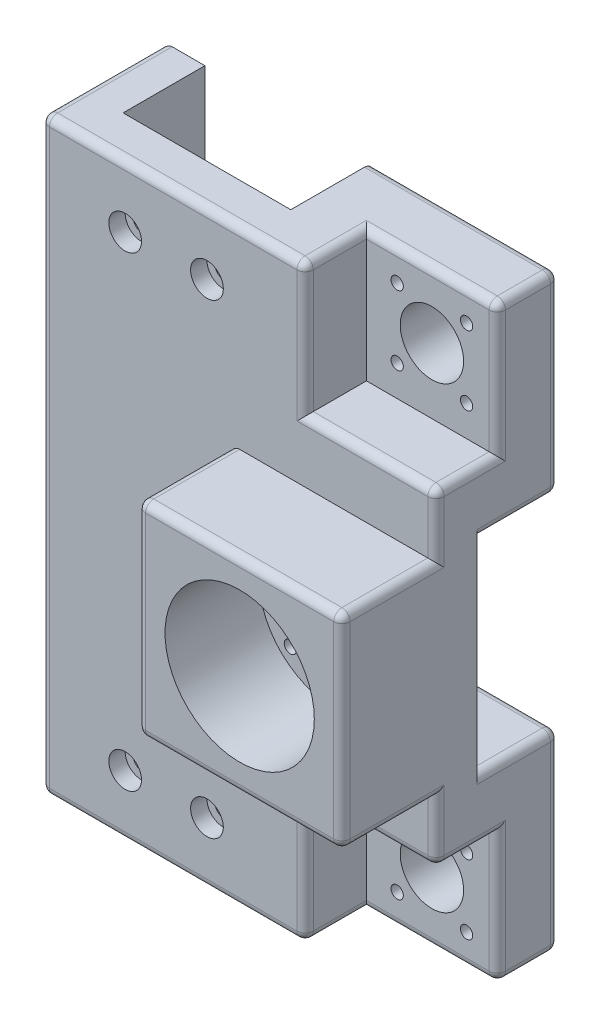
SolidWorks part; units mm, degrees
ref_plane "Front" through (0, 0, 0) normal (0, 0, 1) x (1, 0, 0)
ref_plane "Top" through (0, 0, 0) normal (0, 1, 0) x (1, 0, 0)
ref_plane "Right" through (0, 0, 0) normal (1, 0, 0) x (0, 0, -1)
sketch "Sketch2" plane through (0, 0, 0) normal (0, 0, 1) x (1, 0, 0)
  line L0 (27.25, 72) -> (-59.25, 72)
  line L1 (-43.25, 0) -> (34.25, 0)
  line L3 (12.75, 21.5) -> (55.75, 21.5)
  line L4 (12.75, 21.5) -> (12.75, -21.5)
  line L5 (12.75, -21.5) -> (55.75, -21.5)
  line L6 (55.75, 21.5) -> (55.75, -21.5)
  line L7 (27.25, 72) -> (59.25, 72)
  line L8 (27.25, 72) -> (27.25, 40)
  line L9 (27.25, 40) -> (59.25, 40)
  line L10 (59.25, 72) -> (59.25, 40)
  line L11 (12.75, 21.5) -> (55.75, -21.5) construction
  line L12 (12.75, -21.5) -> (55.75, 21.5) construction
  line L13 (27.25, -40) -> (59.25, -40)
  line L14 (27.25, -40) -> (27.25, -72)
  line L15 (27.25, -72) -> (59.25, -72)
  line L16 (59.25, -40) -> (59.25, -72)
  line L19 (-59.25, 16) -> (-27.25, 16)
  line L20 (-59.25, 16) -> (-59.25, -16)
  line L21 (-59.25, -16) -> (-27.25, -16)
  line L22 (-27.25, 16) -> (-27.25, -16)
  line L25 (-59.25, 72) -> (-59.25, -72)
  line L26 (-59.25, -72) -> (27.25, -72)
  line L27 (59.25, -40) -> (59.25, 40)
  point P0 (0, 0)
  point P14 (-43.25, 0)
sketch "Sketch3" plane through (0, 0, 0) normal (0, 0, 1) x (1, 0, 0)
  line L0 (-59.25, 72) -> (-59.25, -72)
  line L1 (-59.25, -72) -> (59.25, -72)
  line L2 (59.25, -72) -> (59.25, 72)
  line L3 (59.25, 72) -> (-59.25, 72)
extrude "Boss-Extrude1" add sketch "Sketch3" against normal blind 30
sketch "Sketch4" plane through (0, 0, 0) normal (0, 0, 1) x (1, 0, 0)
  circle A0 centre (34.25, 0) radius 11
extrude "Cut-Extrude1" cut sketch "Sketch4" against normal blind 2
sketch "Sketch5" plane through (0, 0, -2) normal (0, 0, 1) x (1, 0, 0)
  circle A0 centre (34.25, 0) radius 4
extrude "Cut-Extrude2" cut sketch "Sketch5" against normal blind 30
sketch "Sketch7" plane through (0, 0, -30) normal (0, 0, -1) x (-1, 0, 0)
  line L2 (27.25, -88.8841) -> (-13.75, -88.8841)
  line L3 (27.25, -88.8841) -> (27.25, 88.8841)
  line L4 (27.25, 88.8841) -> (-13.75, 88.8841)
  line L5 (-13.75, -88.8841) -> (-13.75, 88.8841)
  line L6 (27.25, -88.8841) -> (-13.75, 88.8841) construction
  line L7 (27.25, 88.8841) -> (-13.75, -88.8841) construction
extrude "Cut-Extrude4" cut sketch "Sketch7" against normal blind 20
sketch "Sketch8" plane through (0, 0, -30) normal (0, 0, -1) x (-1, 0, 0)
  line L1 (8.7589, 25) -> (-77.2589, 25)
  line L2 (8.7589, 25) -> (8.7589, -25)
  line L3 (8.7589, -25) -> (-77.2589, -25)
  line L4 (-77.2589, 25) -> (-77.2589, -25)
  line L5 (8.7589, 25) -> (-77.2589, -25) construction
  line L6 (8.7589, -25) -> (-77.2589, 25) construction
  point P0 (-34.25, 0)
extrude "Cut-Extrude5" cut sketch "Sketch8" against normal blind 20
sketch "Sketch9" plane through (0, 0, 0) normal (0, 0, 1) x (1, 0, 0)
  circle A0 centre (-43.25, 0) radius 7.5
  circle A1 centre (43.25, -56) radius 7.5
  circle A2 centre (43.25, 56) radius 7.5
extrude "Cut-Extrude6" cut sketch "Sketch9" against normal blind 30
sketch "Sketch10" plane through (0, 0, 0) normal (0, 0, 1) x (1, 0, 0)
  line L1 (-59.25, 16) -> (-27.25, 16)
  line L2 (-59.25, 16) -> (-59.25, -16)
  line L3 (-59.25, -16) -> (-27.25, -16)
  line L4 (-27.25, 16) -> (-27.25, -16)
  line L5 (-59.25, 16) -> (-27.25, -16) construction
  line L6 (-59.25, -16) -> (-27.25, 16) construction
  line L7 (27.25, 72) -> (59.25, 72)
  line L8 (27.25, 72) -> (27.25, 40)
  line L9 (27.25, 40) -> (59.25, 40)
  line L10 (59.25, 72) -> (59.25, 40)
  line L11 (27.25, 72) -> (59.25, 40) construction
  line L12 (27.25, 40) -> (59.25, 72) construction
  line L13 (27.25, -40) -> (59.25, -40)
  line L14 (27.25, -40) -> (27.25, -72)
  line L15 (27.25, -72) -> (59.25, -72)
  line L16 (59.25, -40) -> (59.25, -72)
  line L17 (27.25, -40) -> (59.25, -72) construction
  line L18 (27.25, -72) -> (59.25, -40) construction
  point P0 (-43.25, 0)
  point P7 (43.25, 56)
  point P14 (43.25, -56)
extrude "Cut-Extrude7" cut sketch "Sketch10" against normal blind 15
sketch "Sketch14" plane through (0, 0, -10) normal (0, 0, -1) x (-1, 0, 0)
  circle A0 centre (16.75, 0) radius 2
  circle A1 centre (-3.25, 0) radius 2
  circle A2 centre (16.75, 57) radius 2
  circle A3 centre (-3.25, 57) radius 2
  circle A4 centre (16.75, -57) radius 2
  circle A5 centre (-3.25, -57) radius 2
  point P6 (6.75, 0)
extrude "Cut-Extrude10" cut sketch "Sketch14" against normal blind 15
sketch "Sketch15" plane through (-59.25, 0, 0) normal (-1, 0, 0) x (0, 0, 1)
  circle A0 centre (-20, 44) radius 2
  circle A1 centre (-20, -44) radius 2
extrude "Cut-Extrude11" cut sketch "Sketch15" against normal blind 34
sketch "Sketch16" plane through (-59.25, 0, 0) normal (-1, 0, 0) x (0, 0, 1)
  circle A0 centre (-20, 44) radius 4
  circle A1 centre (-20, -44) radius 4
extrude "Cut-Extrude12" cut sketch "Sketch16" against normal blind 26
sketch "Sketch17" plane through (0, 0, -15) normal (0, 0, 1) x (1, 0, 0)
  line L1 (-59.25, 16) -> (-27.25, 16)
  line L2 (-59.25, 16) -> (-59.25, -16)
  line L3 (-59.25, -16) -> (-27.25, -16)
  line L4 (-27.25, 16) -> (-27.25, -16)
  line L5 (-59.25, 16) -> (-27.25, -16) construction
  line L6 (-59.25, -16) -> (-27.25, 16) construction
  point P0 (-43.25, 0)
extrude "Boss-Extrude2" add sketch "Sketch17" along normal blind 15
sketch "Sketch18" plane through (0, 72, 0) normal (0, 1, 0) x (1, 0, 0)
  line L0 (-27.25, 30) -> (-27.25, 0)
  line L1 (27.25, 0) -> (-59.25, 0) construction
  line L2 (-27.25, 0) -> (-37.25, 0)
  line L3 (-37.25, 0) -> (-37.25, 30)
  line L4 (-27.25, 30) -> (-59.25, 30) construction
  line L5 (-37.25, 30) -> (-27.25, 30)
extrude "Boss-Extrude3" add sketch "Sketch18" against normal blind 144
sketch "Sketch19" plane through (0, 72, 0) normal (0, 1, 0) x (1, 0, 0)
  line L1 (-27.25, 30) -> (-59.25, 30) construction
  line L2 (-37.25, 30) -> (-37.25, 0)
  line L3 (27.25, 0) -> (-59.25, 0) construction
  line L4 (-37.25, 0) -> (-59.25, 0)
  line L5 (-59.25, 0) -> (-59.25, 30)
  line L6 (-59.25, 30) -> (-37.25, 30)
extrude "Cut-Extrude13" cut sketch "Sketch19" against normal blind 144
sketch "Sketch20" plane through (-27.25, 0, 0) normal (1, 0, 0) x (0, 0, -1)
  circle A0 centre (20, -50) radius 2
  circle A1 centre (20, 0) radius 2
  circle A2 centre (20, 50) radius 2
  point P6 (20, 0)
extrude "Cut-Extrude14" cut sketch "Sketch20" against normal blind 10
sketch "Sketch21" plane through (0, 0, -15) normal (0, 0, 1) x (1, 0, 0)
  circle A0 centre (43.25, -56) radius 7.75
  circle A1 centre (43.25, 56) radius 7.75
extrude "Cut-Extrude15" cut sketch "Sketch21" against normal blind 15
sketch "Sketch22" plane through (-37.25, 0, 0) normal (-1, 0, 0) x (0, 0, 1)
  circle A0 centre (-20, 50) radius 4
  circle A1 centre (-20, 0) radius 4
  circle A2 centre (-20, -50) radius 4
extrude "Cut-Extrude16" cut sketch "Sketch22" against normal blind 4
sketch "Sketch23" plane through (0, 0, 0) normal (0, 0, 1) x (1, 0, 0)
  circle A0 centre (-16.75, 57) radius 4
  circle A1 centre (3.25, 57) radius 4
  circle A2 centre (-16.75, -57) radius 4
  circle A3 centre (3.25, -57) radius 4
extrude "Cut-Extrude17" cut sketch "Sketch23" against normal blind 4
sketch "Sketch24" plane through (0, 0, 0) normal (0, 0, 1) x (1, 0, 0)
  circle A0 centre (-16.75, 0) radius 2
  circle A1 centre (3.25, 0) radius 2
extrude "Boss-Extrude4" add sketch "Sketch24" against normal blind 10
sketch "Sketch25" plane through (0, 0, -2) normal (0, 0, 1) x (1, 0, 0)
  circle A0 centre (34.25, 0) radius 5
extrude "Cut-Extrude18" cut sketch "Sketch25" against normal blind 10
sketch "Sketch26" plane through (0, 0, -15) normal (0, 0, 1) x (1, 0, 0)
  circle A1 centre (34.7647, -64.4853) radius 1.5
  circle A2 centre (34.7647, -47.5147) radius 1.5
  circle A3 centre (51.7353, -47.5147) radius 1.5
  circle A4 centre (51.7353, -64.4853) radius 1.5
  circle A5 centre (34.7647, 47.5147) radius 1.5
  circle A6 centre (51.7353, 47.5147) radius 1.5
  circle A7 centre (51.7353, 64.4853) radius 1.5
  circle A8 centre (34.7647, 64.4853) radius 1.5
extrude "Cut-Extrude19" cut sketch "Sketch26" against normal blind 15
sketch "Sketch27" plane through (0, 0, 0) normal (0, 0, 1) x (1, 0, 0)
  circle A0 centre (34.25, 0) radius 11.25
extrude "Cut-Extrude20" cut sketch "Sketch27" against normal blind 2
sketch "Sketch28" plane through (0, 0, 0) normal (0, 0, 1) x (1, 0, 0)
  line L0 (59.25, -40) -> (59.25, 40) construction
  line L1 (9.25, 25) -> (59.25, 25)
  line L2 (9.25, 25) -> (9.25, -25)
  line L3 (9.25, -25) -> (59.25, -25)
  line L4 (59.25, 25) -> (59.25, -25)
  line L5 (9.25, 25) -> (21.3453, 12.9047) construction
  line L6 (9.25, -25) -> (21.3453, -12.9047) construction
  line L7 (47.1547, 12.9047) -> (59.25, 25) construction
  line L8 (47.1547, -12.9047) -> (59.25, -25) construction
  circle A0 centre (34.25, 0) radius 18.25
extrude "Boss-Extrude5" add sketch "Sketch28" along normal blind 23
sketch "Sketch29" plane through (0, 0, -10) normal (0, 0, -1) x (-1, 0, 0)
  circle A1 centre (-23.6434, 10.6066) radius 1.5
  circle A2 centre (-23.6434, -10.6066) radius 1.5
  circle A3 centre (-44.8566, 10.6066) radius 1.5
  circle A4 centre (-44.8566, -10.6066) radius 1.5
extrude "Cut-Extrude21" cut sketch "Sketch29" against normal blind 10
fillet "Fillet1" radius 2 38 edges at (-37.25, 72, -15) (-37.25, -72, -15) (-37.25, 0, -30) (-37.25, 0, 0) (43.25, -72, -15) (36.5, -72, -30) (36.5, -25, -30) (36.5, 25, -30) (36.5, 72, -30) (-5, 72, 0) (27.25, 56, 0) (43.25, 40, 0) (9.25, 25, 11.5) (9.25, -25, 11.5) (34.25, 25, 23) (9.25, 0, 23) (34.25, -25, 23) (59.25, 0, 23) (43.25, -40, 0) (27.25, -56, 0) (27.25, -72, -7.5) (59.25, -40, -7.5) (27.25, 72, -7.5) (59.25, 40, -7.5) (59.25, 72, -22.5) (59.25, 48.5, -30) (59.25, 25, -20) (59.25, -48.5, -30) (59.25, -25, -20) (59.25, -72, -22.5) (-5, -72, 0) (59.25, -56, -15) (59.25, 56, -15) (43.25, 72, -15)
